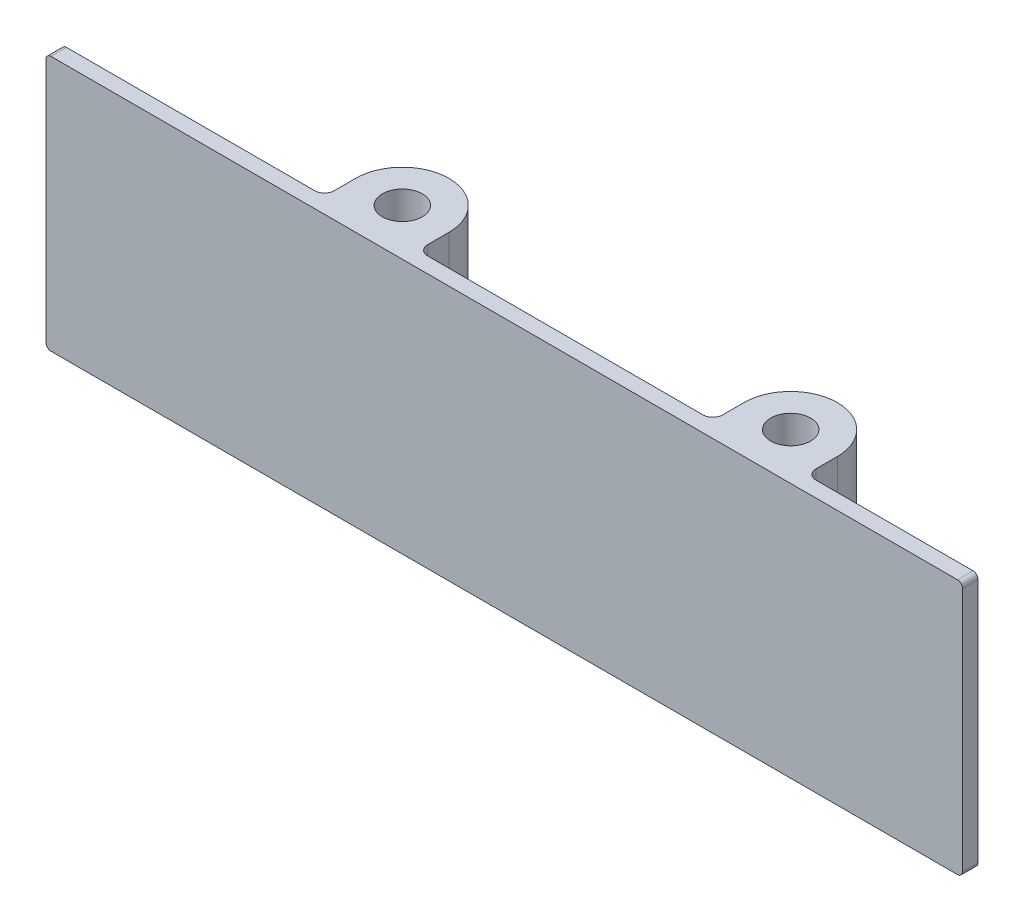
SolidWorks part; units mm, degrees
material "ABS"
ref_plane "X-Y Datum" through (0, 0, 0) normal (0, 0, 1) x (1, 0, 0)
ref_plane "X-Z Datum" through (0, 0, 0) normal (0, 1, 0) x (1, 0, 0)
ref_plane "Y-Z Datum" through (0, 0, 0) normal (1, 0, 0) x (0, 0, -1)
sketch "Sketch2" plane through (0, 0, 0) normal (0, 0, 1) x (1, 0, 0)
  line L1 (0, 0) -> (187.0024, 0)
  line L2 (0, 0) -> (0, 52.1005)
  line L3 (0, 52.1005) -> (187.0024, 52.1005)
  line L4 (187.0024, 0) -> (187.0024, 52.1005)
extrude "Boss-Extrude1" add sketch "Sketch2" along normal blind 3.175
sketch "Sketch4" plane through (0, 52.1005, 0) normal (0, 1, 0) x (1, 0, 0)
  line L0 (0, -3.175) -> (0, 0) construction
  line L1 (53.6474, 0) -> (72.7074, 0)
  line L2 (53.6474, 6.355) -> (53.6474, 0)
  line L3 (187.0024, 0) -> (0, 0) construction
  line L4 (72.7074, 6.355) -> (72.7074, 0)
  line L5 (132.8954, 6.355) -> (132.8954, 0)
  line L6 (151.9554, 6.355) -> (151.9554, 0)
  line L7 (132.8954, 0) -> (151.9554, 0)
  arc A0 (72.7074, 6.355) -> (53.6474, 6.355) centre (63.1774, 6.355) ccw
  arc A1 (151.9554, 6.355) -> (132.8954, 6.355) centre (142.4254, 6.355) ccw
  circle A2 centre (63.1774, 6.355) radius 4.075
  circle A3 centre (142.4254, 6.355) radius 4.075
  dimension "D1" = 63.1774
  dimension "D2" = 142.4254
extrude "Boss-Extrude2" add sketch "Sketch4" against normal through all
fillet "Fillet1" radius 2 4 edges at (53.6474, 26.0502, 0) (132.8954, 26.0502, 0) (151.9554, 26.0502, 0) (72.7074, 26.0502, 0)
fillet "Fillet2" radius 1 4 edges at (187.0024, 0, 1.5875) (187.0024, 52.1005, 1.5875) (0, 0, 1.5875) (0, 52.1005, 1.5875)
